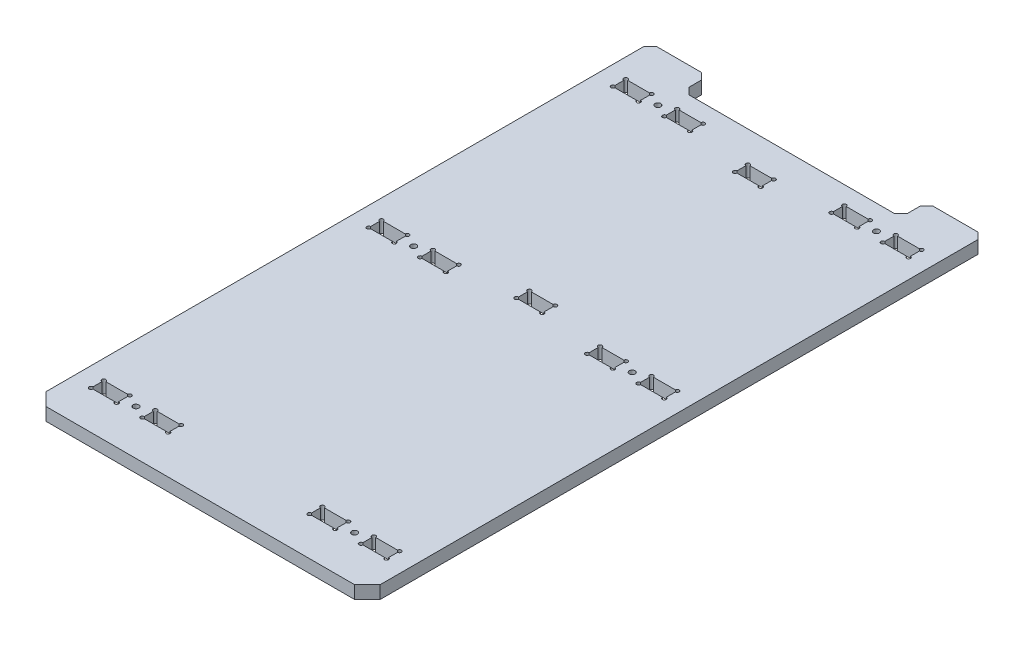
SolidWorks part; units mm, degrees
material "POLICARB. TRANSP."
ref_plane "Front Plane" through (0, 0, 0) normal (0, 0, 1) x (1, 0, 0)
ref_plane "Top Plane" through (0, 0, 0) normal (0, 1, 0) x (1, 0, 0)
ref_plane "Right Plane" through (0, 0, 0) normal (1, 0, 0) x (0, 0, -1)
sketch "Sketch1" plane through (0, 0, 0) normal (0, 1, 0) x (1, 0, 0)
  line L1 (130, 220) -> (-130, 220)
  line L2 (130, 220) -> (130, -220)
  line L3 (130, -220) -> (-130, -220)
  line L4 (-130, 220) -> (-130, -220)
  line L5 (0, -220) -> (0, 220) construction
  line L6 (130, 0) -> (-130, 0) construction
  point P0 (0, 0)
  dimension "D1" = 260
  dimension "D2" = 440
extrude "Extrude1" add sketch "Sketch1" along normal blind 10
sketch "Sketch2" plane through (0, 10, 0) normal (0, 1, 0) x (1, 0, 0)
  line L0 (-130, -220) -> (130, -220) construction
  line L1 (-120, -220) -> (120, -220)
  line L2 (-120, -220) -> (-120, -240)
  line L3 (-120, -240) -> (120, -240)
  line L4 (120, -220) -> (120, -240)
  line L5 (0, 0) -> (0, -220) construction
  line L6 (-130, 220) -> (-130, -220) construction
  dimension "D1" = 20
  dimension "D2" = 10
extrude "Extrude2" [suppressed] add sketch "Sketch2" against normal blind 10
sketch "Sketch3" plane through (0, 10, 0) normal (0, 1, 0) x (1, 0, 0)
  line L0 (130, 220) -> (-130, 220) construction
  line L1 (-130, 220) -> (130, 220)
  line L2 (-130, 220) -> (-130, 260)
  line L3 (-130, 260) -> (130, 260)
  line L4 (130, 220) -> (130, 260)
  line L5 (0, 0) -> (0, 220) construction
  line L7 (130, -220) -> (130, 220) construction
  dimension "D1" = 40
extrude "Extrude3" add sketch "Sketch3" against normal blind 10
extrude "Cut-Extrude1" cut sketch "Sketch4" against normal up to surface (10 mm away) up to face at (0, 10, -20)
sketch "Sketch4" plane through (130, 0, -206) normal (0, -1, 0) x (1, 0, 0)
  line L0 (-260, -54) -> (-260, 426) construction
  line L1 (-245, 396) -> (-225, 396)
  line L2 (-245, 396) -> (-245, 386)
  line L3 (-245, 386) -> (-225, 386)
  line L4 (-225, 396) -> (-225, 386)
  line L5 (-205, 396) -> (-185, 396)
  line L6 (-205, 396) -> (-205, 386)
  line L7 (-205, 386) -> (-185, 386)
  line L8 (-185, 396) -> (-185, 386)
  line L9 (-75, 396) -> (-55, 396)
  line L10 (-75, 396) -> (-75, 386)
  line L11 (-75, 386) -> (-55, 386)
  line L12 (-55, 396) -> (-55, 386)
  line L13 (-35, 396) -> (-15, 396)
  line L14 (-35, 396) -> (-35, 386)
  line L15 (-35, 386) -> (-15, 386)
  line L16 (-15, 396) -> (-15, 386)
  line L17 (-245, 180) -> (-225, 180)
  line L18 (-245, 180) -> (-245, 170)
  line L19 (-245, 170) -> (-225, 170)
  line L20 (-225, 180) -> (-225, 170)
  line L21 (-260, 426) -> (0, 426) construction
  line L22 (-205, 180) -> (-185, 180)
  line L23 (-205, 180) -> (-205, 170)
  line L24 (-205, 170) -> (-185, 170)
  line L25 (-185, 180) -> (-185, 170)
  line L26 (-75, 180) -> (-55, 180)
  line L27 (-75, 180) -> (-75, 170)
  line L28 (-75, 170) -> (-55, 170)
  line L29 (-55, 180) -> (-55, 170)
  line L30 (-35, 180) -> (-15, 180)
  line L31 (-35, 180) -> (-35, 170)
  line L32 (-35, 170) -> (-15, 170)
  line L33 (-15, 180) -> (-15, 170)
  line L35 (-245, -10) -> (-225, -10)
  line L36 (-245, -10) -> (-245, -20)
  line L37 (-245, -20) -> (-225, -20)
  line L38 (-225, -10) -> (-225, -20)
  line L39 (-205, -10) -> (-185, -10)
  line L40 (-205, -10) -> (-205, -20)
  line L41 (-205, -20) -> (-185, -20)
  line L42 (-185, -10) -> (-185, -20)
  line L44 (-75, -10) -> (-55, -10)
  line L45 (-75, -10) -> (-75, -20)
  line L46 (-75, -20) -> (-55, -20)
  line L47 (-55, -10) -> (-55, -20)
  line L48 (-35, -10) -> (-15, -10)
  line L49 (-35, -10) -> (-35, -20)
  line L50 (-35, -20) -> (-15, -20)
  line L51 (-15, -10) -> (-15, -20)
  dimension "D1" = 20
  dimension "D2" = 10
  dimension "D3" = 15
  dimension "D4" = 30
  dimension "D5" = 216
  dimension "D6" = 190
  dimension "D7" = 20
  dimension "D8" = 110
  dimension "D9" = 20
  dimension "D10" = 10
  dimension "D11" = 15
  dimension "D12" = 20
  dimension "D13" = 110
  dimension "D14" = 20
  dimension "D15" = 20
  dimension "D16" = 10
  dimension "D17" = 20
  dimension "D18" = 20
  dimension "D19" = 15
  dimension "D20" = 110
  dimension "D21" = 20
sketch "Sketch5" plane through (0, 0, 0) normal (0, -1, 0) x (-1, 0, 0)
  line L0 (96.5, -190) -> (95, -190)
  line L1 (115, -190) -> (113.5, -190)
  line L2 (115, -190) -> (115, -188.5)
  line L3 (115, -180) -> (113.5, -180)
  line L4 (95, -190) -> (95, -188.5)
  line L5 (115, -181.5) -> (115, -180)
  line L6 (96.5, -180) -> (95, -180)
  line L7 (95, -181.5) -> (95, -180)
  arc A0 (113.5, -190) -> (115, -188.5) centre (115, -190) ccw
  arc A1 (115, -181.5) -> (113.5, -180) centre (115, -180) ccw
  arc A2 (96.5, -180) -> (95, -181.5) centre (95, -180) ccw
  arc A3 (95, -188.5) -> (96.5, -190) centre (95, -190) ccw
  dimension "D1" = 3
extrude "Extrude4" cut sketch "Sketch5" against normal blind 10
ref_plane "Plane1" through (-85, 0, 0) normal (1, 0, 0) x (0, 0, -1)
mirror "Mirror1" about plane through (-85, 0, 0) normal (1, 0, 0) of "Extrude4"
ref_plane "Plane2" through (0, 0, 0) normal (1, 0, 0) x (0, 0, -1)
mirror "Mirror2" about plane through (0, 0, 0) normal (1, 0, 0) of "Mirror1", "Extrude4"
ref_plane "Plane3" through (0, 0, 77) normal (0, 0, -1) x (-1, 0, 0)
mirror "Mirror3" about plane through (0, 0, 77) normal (0, 0, -1) of "Mirror2", "Mirror1", "Extrude4"
ref_plane "Plane4" through (0, 0, -18) normal (0, 0, 1) x (1, 0, 0)
mirror "Mirror4" about plane through (0, 0, -18) normal (0, 0, 1) of "Mirror2", "Extrude4", "Mirror1"
hole_wizard "M4 Clearance Hole1" positions "Sketch6" profile "Sketch7" hole size "M4" standard "DIN" end condition through all
sketch "Sketch6" plane through (0, 10, 0) normal (0, 1, 0) x (1, 0, 0)
  line L4 (-95, 221) -> (-75, 221) construction
  line L5 (-95, 217.5) -> (-95, 224.5) construction
  line L6 (-75, 224.5) -> (-75, 217.5) construction
  line L8 (75, 217.5) -> (75, 224.5) construction
  line L9 (75, 221) -> (95, 221) construction
  line L10 (95, 224.5) -> (95, 217.5) construction
  line L14 (-95, 27.5) -> (-95, 34.5) construction
  line L15 (-95, 31) -> (-75, 31) construction
  line L16 (-75, 34.5) -> (-75, 27.5) construction
  line L18 (-95, -185) -> (-75, -185) construction
  line L19 (-95, -188.5) -> (-95, -181.5) construction
  line L20 (-75, -181.5) -> (-75, -188.5) construction
  point P0 (-85, 221)
  point P2 (85, 221)
  point P4 (85, 31)
  point P6 (-85, 31)
  point P8 (-85, -185)
  point P10 (85, -185)
  point P61 (0, 0)
sketch "Sketch7" plane through (-85, 10, -221) normal (1, 0, 0) x (0, 0, 1)
  line L0 (0, 0) -> (0, 10)
  line L1 (0, 10) -> (2.25, 10)
  line L2 (2.25, 10) -> (2.25, 0)
  line L5 (2.25, 0) -> (0, 0)
  line L11 (0, -6.35) -> (0, 107.95) construction
  dimension "Thru Hole Dia." = 4.5
  dimension "Thru Hole Depth" = 10
extrude "Cut-Extrude2" cut sketch "Sketch8" against normal blind 10
sketch "Sketch8" plane through (130, 0, -206) normal (0, -1, 0) x (1, 0, 0)
  line L0 (-130, 206) -> (-130, -54) construction
  line L1 (0, -54) -> (-260, -54) construction
  line L2 (-140, 170) -> (-120, 170)
  line L3 (-140, 170) -> (-140, 160)
  line L4 (-140, 160) -> (-120, 160)
  line L5 (-120, 170) -> (-120, 160)
  line L7 (-140, 0) -> (-120, 0)
  line L8 (-140, 0) -> (-140, -10)
  line L9 (-140, -10) -> (-120, -10)
  line L10 (-120, 0) -> (-120, -10)
  dimension "D1" = 20
  dimension "D2" = 44
  dimension "D3" = 160
  dimension "D4" = 10
sketch "Sketch9" plane through (0, 0, 0) normal (0, -1, 0) x (1, 0, 0)
  line L0 (-10, -44.5) -> (-10, -46)
  line L1 (-10, -36) -> (-8.5, -36)
  line L2 (-10, -36) -> (-10, -37.5)
  line L3 (-10, -46) -> (-8.5, -46)
  line L4 (10, -36) -> (10, -37.5)
  line L5 (8.5, -46) -> (10, -46)
  line L6 (10, -44.5) -> (10, -46)
  line L7 (8.5, -36) -> (10, -36)
  arc A0 (-8.5, -36) -> (-10, -37.5) centre (-10, -36) ccw
  arc A1 (10, -37.5) -> (8.5, -36) centre (10, -36) ccw
  arc A2 (8.5, -46) -> (10, -44.5) centre (10, -46) ccw
  arc A3 (-10, -44.5) -> (-8.5, -46) centre (-10, -46) ccw
  dimension "D1" = 3
extrude "Extrude5" cut sketch "Sketch9" against normal blind 10
ref_plane "Plane5" through (0, 0, -126) normal (0, 0, 1) x (1, 0, 0)
mirror "Mirror5" about plane through (0, 0, -126) normal (0, 0, 1) of "Extrude5"
chamfer "Chamfer1" distance 10 angle 45 2 edges at (-130, 5, 220) (130, 5, 220)
sketch "Sketch10" plane through (0, 10, 0) normal (0, 1, 0) x (1, 0, 0)
  line L0 (130, 260) -> (-130, 260) construction
  line L1 (-85, 260) -> (85, 260)
  line L2 (-85, 260) -> (-85, 240)
  line L3 (-85, 240) -> (85, 240)
  line L4 (85, 260) -> (85, 240)
  line L5 (0, 0) -> (0, 260) construction
  line L6 (-130, 260) -> (-130, -210) construction
  dimension "D1" = 45
  dimension "D2" = 20
extrude "Extrude6" cut sketch "Sketch10" against normal blind 10
chamfer "Chamfer2" distance 5 angle 45 6 edges at (85, 5, -240) (-85, 5, -240) (-130, 5, -260) (-85, 5, -260) (85, 5, -260) (130, 5, -260)
